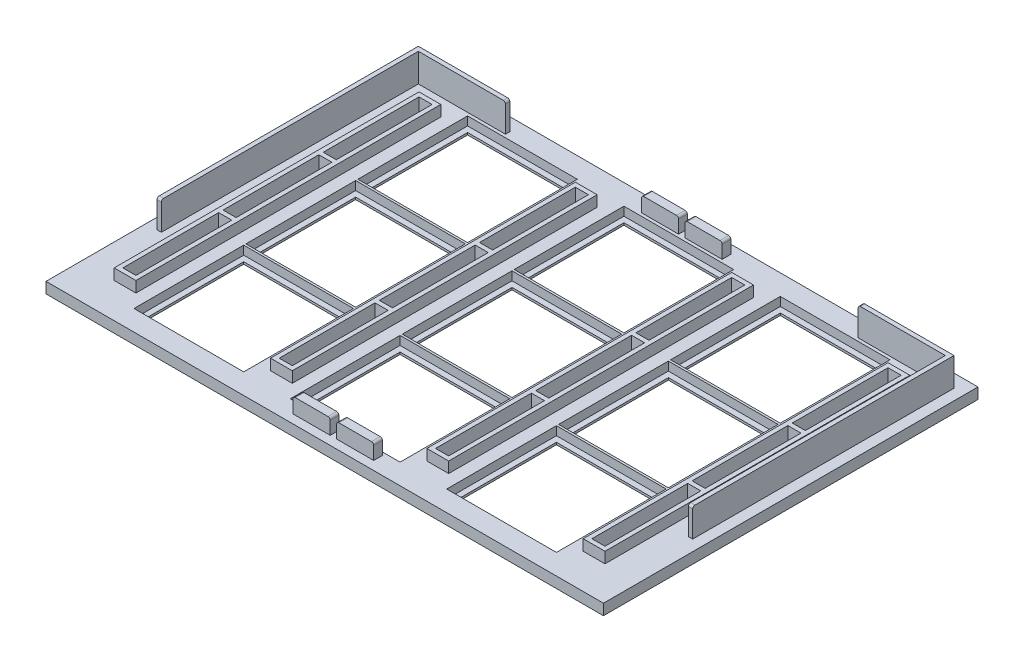
SolidWorks part; units mm, degrees
ref_plane "Front Plane" through (0, 0, 0) normal (0, 0, 1) x (1, 0, 0)
ref_plane "Top Plane" through (0, 0, 0) normal (0, 1, 0) x (1, 0, 0)
ref_plane "Right Plane" through (0, 0, 0) normal (1, 0, 0) x (0, 0, -1)
sketch "Sketch2" plane through (0, 0, 0) normal (0, 1, 0) x (1, 0, 0)
  line L2 (-64, 43) -> (64, 43)
  line L3 (64, 43) -> (64, -43)
  line L4 (-64, 43) -> (-64, -43)
  line L5 (-64, -43) -> (64, -43)
  point P4 (0, 0)
  point P8 (0, 0)
  dimension "D1" = 128
  dimension "D2" = 86
extrude "Boss-Extrude1" add sketch "Sketch2" against normal blind 2.5
sketch "Sketch3" plane through (0, 0, 0) normal (0, 1, 0) x (1, 0, 0)
  line L0 (12.6, 0) -> (-12.6, 0)
  line L1 (-12.6, 0) -> (-23.3, 0)
  line L2 (-23.3, 0) -> (-48.5, 0)
  line L3 (-48.5, 0) -> (-60.5, 0)
  line L4 (12.6, 0) -> (23.3, 0)
  line L5 (23.3, 0) -> (48.5, 0)
  line L6 (48.5, 0) -> (60.5, 0)
  line L7 (-12.6, 12.6) -> (-12.6, -12.6)
  line L8 (-12.6, 12.6) -> (-12.6, 13.1)
  line L9 (-12.6, 12.6) -> (12.6, 12.6)
  line L10 (-12.6, 12.6) -> (-12.6, -12.6)
  line L11 (-12.6, -12.6) -> (12.6, -12.6)
  line L12 (12.6, 12.6) -> (12.6, -12.6)
  line L13 (-12.6, 13.1) -> (12.6, 13.1)
  line L14 (-12.6, -12.6) -> (-12.6, -13.1)
  line L15 (-12.6, 13.1) -> (12.6, 13.1)
  line L16 (-12.6, 13.1) -> (-12.6, 38.3)
  line L17 (-12.6, 38.3) -> (12.6, 38.3)
  line L18 (12.6, 13.1) -> (12.6, 38.3)
  line L19 (-12.6, -13.1) -> (-12.6, -38.3)
  line L21 (-12.6, -38.3) -> (12.6, -38.3)
  line L22 (-12.6, -38.3) -> (-12.6, -13.1)
  line L23 (-12.6, -13.1) -> (12.6, -13.1)
  line L24 (12.6, -38.3) -> (12.6, -13.1)
  line L25 (48.5, -13.1) -> (23.3, -13.1)
  line L26 (23.3, -38.3) -> (23.3, -13.1)
  line L27 (48.5, -38.3) -> (23.3, -38.3)
  line L28 (48.5, -38.3) -> (48.5, -13.1)
  line L29 (48.5, -12.6) -> (23.3, -12.6)
  line L30 (23.3, 12.6) -> (23.3, -12.6)
  line L31 (48.5, 12.6) -> (23.3, 12.6)
  line L32 (48.5, 12.6) -> (48.5, -12.6)
  line L33 (48.5, 38.3) -> (23.3, 38.3)
  line L34 (23.3, 13.1) -> (23.3, 38.3)
  line L35 (48.5, 13.1) -> (23.3, 13.1)
  line L36 (48.5, 13.1) -> (48.5, 38.3)
  line L37 (-23.3, -13.1) -> (-48.5, -13.1)
  line L38 (-48.5, -38.3) -> (-48.5, -13.1)
  line L39 (-23.3, -38.3) -> (-48.5, -38.3)
  line L40 (-23.3, -38.3) -> (-23.3, -13.1)
  line L41 (-23.3, -12.6) -> (-48.5, -12.6)
  line L42 (-48.5, 12.6) -> (-48.5, -12.6)
  line L43 (-23.3, 12.6) -> (-48.5, 12.6)
  line L44 (-23.3, 12.6) -> (-23.3, -12.6)
  line L45 (-23.3, 38.3) -> (-48.5, 38.3)
  line L46 (-48.5, 13.1) -> (-48.5, 38.3)
  line L47 (-23.3, 13.1) -> (-48.5, 13.1)
  line L48 (-23.3, 13.1) -> (-23.3, 38.3)
  point P4 (0, 0)
  point P6 (0, 0)
  point P8 (0, 0)
  point P15 (-12.6, 0)
  point P16 (-12.6, 0)
  dimension "D1" = 25.2
  dimension "D2" = 10.7
  dimension "D3" = 25.2
  dimension "D4" = 12
  dimension "D5" = 10.7
  dimension "D6" = 25.2
  dimension "D7" = 12
  dimension "D8" = 25.2
  dimension "D9" = 0.5
  dimension "D10" = 25.2
  dimension "D11" = 0.5
  dimension "D12" = 25.2
extrude "Cut-Extrude1" cut sketch "Sketch3" against normal blind 2 contours L13 L18 L17 L16 | L35 L36 L33 L34 | L32 L31 L30 L5 | L32 L5 L30 L29 | L27 L28 L25 L26 | L12 L9 L7 L0 | L12 L0 L7 L11 | L21 L24 L23 L19 | L47 L48 L45 L46 | L44 L43 L42 L2 | L44 L2 L42 L41 | L39 L40 L37 L38
sketch "Sketch4" plane through (0, 0, 0) normal (0, 1, 0) x (1, 0, 0)
  line L1 (-11.3, -11.3) -> (11.3, -11.3)
  line L2 (-11.3, -11.3) -> (-11.3, 11.3)
  line L3 (-11.3, 11.3) -> (11.3, 11.3)
  line L4 (11.3, -11.3) -> (11.3, 11.3)
  line L5 (-11.3, -11.3) -> (11.3, 11.3) construction
  line L6 (-11.3, 11.3) -> (11.3, -11.3) construction
  line L8 (-11.3, 14.4) -> (11.3, 14.4)
  line L9 (11.3, 37) -> (11.3, 14.4)
  line L10 (-11.3, 37) -> (11.3, 37)
  line L11 (-11.3, 37) -> (-11.3, 14.4)
  line L15 (-11.3, -37) -> (11.3, -37)
  line L16 (11.3, -14.4) -> (11.3, -37)
  line L17 (-11.3, -14.4) -> (11.3, -14.4)
  line L18 (-11.3, -14.4) -> (-11.3, -37)
  line L19 (47.2, -14.4) -> (47.2, -37)
  line L20 (47.2, -14.4) -> (24.6, -14.4)
  line L21 (24.6, -14.4) -> (24.6, -37)
  line L22 (47.2, -37) -> (24.6, -37)
  line L23 (47.2, 11.3) -> (24.6, 11.3)
  line L24 (24.6, -11.3) -> (24.6, 11.3)
  line L25 (47.2, -11.3) -> (24.6, -11.3)
  line L26 (47.2, -11.3) -> (47.2, 11.3)
  line L27 (47.2, 37) -> (47.2, 14.4)
  line L28 (47.2, 37) -> (24.6, 37)
  line L29 (24.6, 37) -> (24.6, 14.4)
  line L30 (47.2, 14.4) -> (24.6, 14.4)
  line L31 (-24.6, -14.4) -> (-24.6, -37)
  line L32 (-24.6, -14.4) -> (-47.2, -14.4)
  line L33 (-47.2, -14.4) -> (-47.2, -37)
  line L34 (-24.6, -37) -> (-47.2, -37)
  line L35 (-24.6, 11.3) -> (-47.2, 11.3)
  line L36 (-47.2, -11.3) -> (-47.2, 11.3)
  line L37 (-24.6, -11.3) -> (-47.2, -11.3)
  line L38 (-24.6, -11.3) -> (-24.6, 11.3)
  line L39 (-24.6, 37) -> (-24.6, 14.4)
  line L40 (-24.6, 37) -> (-47.2, 37)
  line L41 (-47.2, 37) -> (-47.2, 14.4)
  line L42 (-24.6, 14.4) -> (-47.2, 14.4)
  point P0 (0, 0)
  dimension "D1" = 22.6
  dimension "D2" = 22.6
extrude "Cut-Extrude2" cut sketch "Sketch4" against normal blind 2.5
sketch "Sketch5" plane through (0, 0, 0) normal (0, 1, 0) x (1, 0, 0)
  line L1 (-23.3, -38.3) -> (-12.6, -38.3)
  line L2 (-12.6, -13.1) -> (-12.6, -38.3) construction
  line L3 (-20.45, 35) -> (-15.45, 35)
  line L5 (-35.9, 37) -> (-35.9, 14.4)
  line L6 (-20.45, 35) -> (-15.45, 35)
  line L7 (-20.45, 35) -> (-20.45, -35)
  line L8 (-20.45, -35) -> (-15.45, -35)
  line L9 (-15.45, 35) -> (-15.45, -35)
  line L10 (-24.6, 37) -> (-47.2, 37) construction
  line L11 (-47.2, 14.4) -> (-24.6, 14.4) construction
  line L12 (0, 37) -> (0, 14.4)
  line L13 (11.3, 37) -> (-11.3, 37) construction
  line L14 (-11.3, 14.4) -> (11.3, 14.4) construction
  line L15 (35.9, 37) -> (35.9, 14.4)
  line L16 (47.2, 37) -> (24.6, 37) construction
  line L17 (24.6, 14.4) -> (47.2, 14.4) construction
  line L18 (20.45, -35) -> (15.45, -35)
  line L19 (15.45, 35) -> (15.45, -35)
  line L20 (20.45, 35) -> (15.45, 35)
  line L21 (20.45, 35) -> (20.45, -35)
  line L22 (51.35, 35) -> (51.35, -35)
  line L23 (51.35, 35) -> (56.35, 35)
  line L24 (56.35, 35) -> (56.35, -35)
  line L25 (51.35, -35) -> (56.35, -35)
  line L26 (-51.35, -35) -> (-56.35, -35)
  line L27 (-56.35, 35) -> (-56.35, -35)
  line L28 (-51.35, 35) -> (-56.35, 35)
  line L29 (-51.35, 35) -> (-51.35, -35)
  point P14 (-17.95, 0)
  dimension "D2" = 5
extrude "Boss-Extrude2" add sketch "Sketch5" along normal blind 2.5 contours L29 L28 L27 L26 | L9 L3 L7 L8 | L21 L20 L19 L18 | L22 L25 L24 L23
ref_plane "Plane1" through (0, 2.5, 0) normal (0, 1, 0) x (1, 0, 0)
sketch "Sketch7" plane through (0, 2.5, 0) normal (0, 1, 0) x (1, 0, 0)
  line L0 (-11.3, 37) -> (11.3, 37)
  line L4 (11.3, 37) -> (0, 37)
  line L7 (-19.45, 11) -> (-16.45, 11)
  line L8 (-19.45, 11) -> (-19.45, -11)
  line L9 (-19.45, -11) -> (-16.45, -11)
  line L10 (-16.45, 11) -> (-16.45, -11)
  line L11 (24.6, 37) -> (47.2, 37)
  line L12 (-19.45, 34) -> (-16.45, 34)
  line L13 (-16.45, 12) -> (-16.45, 34)
  line L14 (-19.45, 12) -> (-16.45, 12)
  line L15 (-19.45, 12) -> (-19.45, 34)
  line L16 (-19.45, -12) -> (-16.45, -12)
  line L17 (-16.45, -12) -> (-16.45, -34)
  line L18 (-19.45, -34) -> (-16.45, -34)
  line L19 (-19.45, -12) -> (-19.45, -34)
  line L21 (-47.2, 37) -> (-24.6, 37)
  line L23 (-52.35, -12) -> (-52.35, -34)
  line L24 (-52.35, -34) -> (-55.35, -34)
  line L25 (-55.35, -12) -> (-55.35, -34)
  line L26 (-52.35, -12) -> (-55.35, -12)
  line L27 (-52.35, -11) -> (-55.35, -11)
  line L28 (-55.35, 11) -> (-55.35, -11)
  line L29 (-52.35, 11) -> (-55.35, 11)
  line L30 (-52.35, 11) -> (-52.35, -11)
  line L31 (-52.35, 12) -> (-55.35, 12)
  line L32 (-55.35, 12) -> (-55.35, 34)
  line L33 (-52.35, 34) -> (-55.35, 34)
  line L34 (-52.35, 12) -> (-52.35, 34)
  line L35 (19.45, -12) -> (19.45, -34)
  line L36 (19.45, -34) -> (16.45, -34)
  line L37 (16.45, -12) -> (16.45, -34)
  line L38 (19.45, -12) -> (16.45, -12)
  line L39 (19.45, -11) -> (16.45, -11)
  line L40 (16.45, 11) -> (16.45, -11)
  line L41 (19.45, 11) -> (16.45, 11)
  line L42 (19.45, 11) -> (19.45, -11)
  line L43 (19.45, 12) -> (16.45, 12)
  line L44 (16.45, 12) -> (16.45, 34)
  line L45 (19.45, 34) -> (16.45, 34)
  line L46 (19.45, 12) -> (19.45, 34)
  line L47 (52.35, -12) -> (55.35, -12)
  line L48 (55.35, -12) -> (55.35, -34)
  line L49 (52.35, -34) -> (55.35, -34)
  line L50 (52.35, -12) -> (52.35, -34)
  line L51 (52.35, 11) -> (52.35, -11)
  line L52 (52.35, 11) -> (55.35, 11)
  line L53 (55.35, 11) -> (55.35, -11)
  line L54 (52.35, -11) -> (55.35, -11)
  line L55 (52.35, 12) -> (52.35, 34)
  line L56 (52.35, 34) -> (55.35, 34)
  line L57 (55.35, 12) -> (55.35, 34)
  line L58 (52.35, 12) -> (55.35, 12)
  point P11 (-17.95, 0)
  point P14 (-17.95, 0)
  dimension "D3" = 1
extrude "Cut-Extrude6" cut sketch "Sketch7" against normal blind 3 contours L15 L14 L13 L12 | L10 L7 L8 L9 | L16 L19 L18 L17 | L43 L46 L45 L44 | L42 L41 L40 L39 | L35 L38 L37 L36 | L55 L58 L57 L56 | L51 L54 L53 L52 | L31 L34 L33 L32 | L30 L29 L28 L27 | L23 L26 L25 L24 | L48 L49 L50 L47
sketch "Sketch9" plane through (0, 0, 0) normal (0, 1, 0) x (1, 0, 0)
  line L0 (-61.5, -20) -> (-60.5, -20)
  line L4 (-40.5, 40) -> (-40.5, 39)
  line L7 (-61.5, 40) -> (-61.5, -20)
  line L8 (-60.5, -20) -> (-60.5, 39)
  line L9 (-60.5, 39) -> (-40.5, 39)
  line L11 (-40.5, 40) -> (-61.5, 40)
  line L12 (40.5, 40) -> (61.5, 40)
  line L13 (61.5, 40) -> (61.5, -20)
  line L14 (61.5, -20) -> (60.5, -20)
  line L15 (60.5, -20) -> (60.5, 39)
  line L16 (60.5, 39) -> (40.5, 39)
  line L17 (40.5, 40) -> (40.5, 39)
  line L28 (-0.75, 39) -> (-9.25, 39)
  line L29 (-0.75, 39) -> (-0.75, 41)
  line L30 (-0.75, 41) -> (-9.25, 41)
  line L31 (-9.25, 39) -> (-9.25, 41)
  line L32 (9.25, 41) -> (0.75, 41)
  line L33 (9.25, 41) -> (9.25, 39)
  line L34 (9.25, 39) -> (0.75, 39)
  line L35 (0.75, 41) -> (0.75, 39)
  line L36 (-0.75, -41) -> (-9.25, -41)
  line L37 (-9.25, -39) -> (-9.25, -41)
  line L38 (-0.75, -39) -> (-9.25, -39)
  line L39 (-0.75, -39) -> (-0.75, -41)
  line L40 (9.25, -39) -> (0.75, -39)
  line L41 (0.75, -41) -> (0.75, -39)
  line L42 (9.25, -41) -> (0.75, -41)
  line L43 (9.25, -41) -> (9.25, -39)
  point P3 (0, 40)
  point P9 (0, 0)
  point P12 (0, 0)
  point P17 (0, 39)
  point P32 (0, 39)
  dimension "D5" = 20
  dimension "D1" = 60
  dimension "D4" = 1
  dimension "D6" = 59
  dimension "D7" = 21
extrude "Boss-Extrude3" add sketch "Sketch9" along normal blind 6.5
sketch "Sketch10" plane through (0, 0, 0) normal (0, 1, 0) x (1, 0, 0)
  line L1 (-9.25, 41) -> (-0.75, 41)
  line L2 (-9.25, 41) -> (-9.25, 39)
  line L3 (-9.25, 39) -> (-0.75, 39)
  line L4 (-0.75, 41) -> (-0.75, 39)
  line L5 (0.75, 41) -> (9.25, 41)
  line L6 (0.75, 41) -> (0.75, 39)
  line L7 (0.75, 39) -> (9.25, 39)
  line L8 (9.25, 41) -> (9.25, 39)
  line L9 (-9.25, -39) -> (-0.75, -39)
  line L10 (-9.25, -39) -> (-9.25, -41)
  line L11 (-9.25, -41) -> (-0.75, -41)
  line L12 (-0.75, -39) -> (-0.75, -41)
  line L13 (0.75, -39) -> (9.25, -39)
  line L14 (0.75, -39) -> (0.75, -41)
  line L15 (0.75, -41) -> (9.25, -41)
  line L16 (9.25, -39) -> (9.25, -41)
extrude "Cut-Extrude9" cut sketch "Sketch10" along normal through all from offset 3.5 contours L2 L1 L4 L3 | L6 L5 L8 L7 | L10 L9 L12 L11 | L14 L13 L16 L15
fillet "Fillet1" radius 0.5 12 edges at (-61, 6.5, 20) (-40.5, 6.5, -39.5) (-0.75, 3.5, -40) (-9.25, 3.5, -40) (0.75, 3.5, -40) (9.25, 3.5, -40) (40.5, 6.5, -39.5) (61, 6.5, 20) (9.25, 3.5, 40) (-9.25, 3.5, 40) (-0.75, 3.5, 40) (0.75, 3.5, 40)
